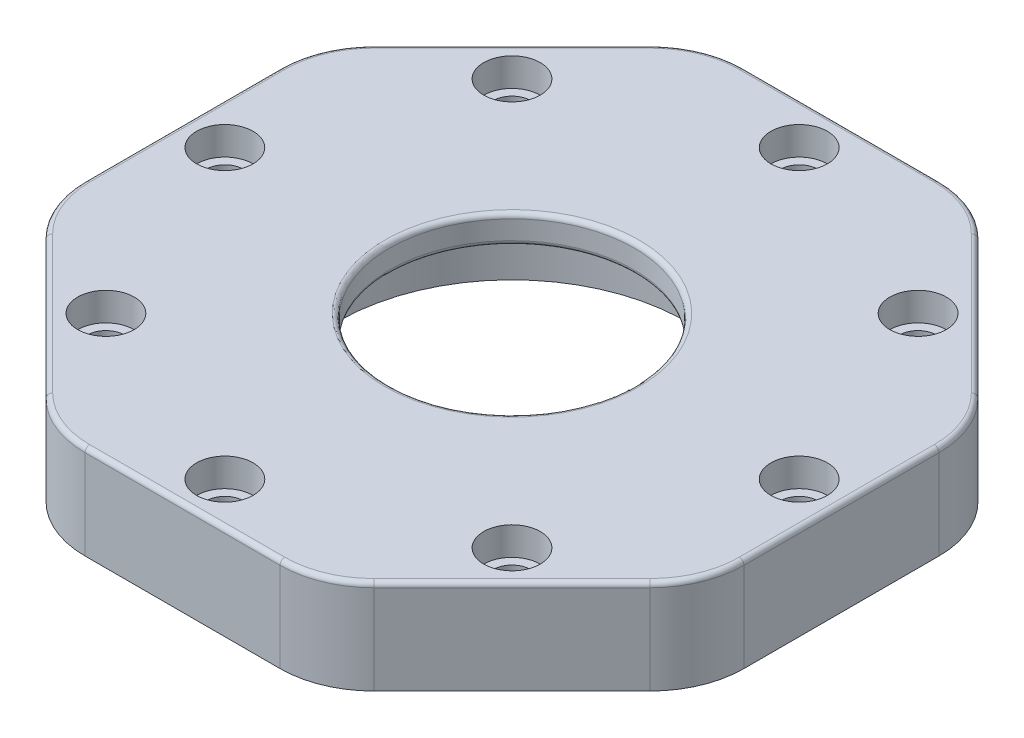
SolidWorks part; units mm, degrees
ref_plane "Front Plane" through (0, 0, 0) normal (0, 0, 1) x (1, 0, 0)
ref_plane "Top Plane" through (0, 0, 0) normal (0, 1, 0) x (1, 0, 0)
ref_plane "Right Plane" through (0, 0, 0) normal (1, 0, 0) x (0, 0, -1)
sketch "Sketch1" plane through (0, 0, 0) normal (0, 1, 0) x (1, 0, 0)
  line L0 (0, 0) -> (-47063.1739, 0) construction
  line L1 (0, 0) -> (0, -47063.1739) construction
  circle A0 centre (0, 0) radius 32
  dimension "D1" = 64
extrude "Boss-Extrude1" add sketch "Sketch1" along normal blind 10
sketch "Sketch2" plane through (0, 10, 0) normal (0, 1, 0) x (1, 0, 0)
  line L0 (0, 0) -> (-50000, 0) construction
  line L1 (0, 0) -> (0, -50000) construction
  circle A0 centre (0, 0) radius 18.5
  dimension "D1" = 37
extrude "Cut-Extrude1" cut sketch "Sketch2" along normal blind 7 from offset 10 offset against normal yes
sketch "Sketch3" plane through (0, 7, 0) normal (0, -1, 0) x (-1, 0, 0)
  line L0 (0, 0) -> (-50000, 0) construction
  line L1 (0, 0) -> (0, -50000) construction
  circle A0 centre (0, 0) radius 13
  dimension "D1" = 26
extrude "Cut-Extrude2" cut sketch "Sketch3" against normal through all
sketch "Sketch6" plane through (0, 0, 0) normal (0, 1, 0) x (1, 0, 0)
  line L0 (0, 0) -> (-50000, 0) construction
  line L1 (0, 0) -> (0, -50000) construction
  line L10 (10.3553, 35) -> (-10.3553, 35)
  line L11 (-17.4264, 32.0711) -> (-32.0711, 17.4264)
  line L12 (-35, 10.3553) -> (-35, -10.3553)
  line L13 (35, 10.3553) -> (35, -10.3553)
  line L14 (17.4264, 32.0711) -> (32.0711, 17.4264)
  line L15 (17.4264, -32.0711) -> (32.0711, -17.4264)
  line L16 (-17.4264, -32.0711) -> (-32.0711, -17.4264)
  line L17 (10.3553, -35) -> (-10.3553, -35)
  circle A10 centre (0, 0) radius 32 construction
  circle A11 centre (0, 0) radius 32
  circle A12 centre (0, 0) radius 35 construction
  arc A13 (-32.0711, 17.4264) -> (-35, 10.3553) centre (-25, 10.3553) ccw
  arc A14 (-32.0711, -17.4264) -> (-35, -10.3553) centre (-25, -10.3553) cw
  arc A15 (-17.4264, -32.0711) -> (-10.3553, -35) centre (-10.3553, -25) ccw
  arc A16 (17.4264, -32.0711) -> (10.3553, -35) centre (10.3553, -25) cw
  arc A17 (32.0711, -17.4264) -> (35, -10.3553) centre (25, -10.3553) ccw
  arc A18 (35, 10.3553) -> (32.0711, 17.4264) centre (25, 10.3553) ccw
  arc A19 (17.4264, 32.0711) -> (10.3553, 35) centre (10.3553, 25) ccw
  arc A20 (-10.3553, 35) -> (-17.4264, 32.0711) centre (-10.3553, 25) ccw
  point P9 (0, -35)
  point P16 (0, 35)
  point P19 (35, 0)
  point P20 (-35, 0)
  point P23 (-35, 14.4975)
  point P26 (-35, -14.4975)
  point P29 (-14.4975, -35)
  point P32 (14.4975, -35)
  point P35 (35, -14.4975)
  point P38 (35, 14.4975)
  point P41 (14.4975, 35)
  point P44 (-14.4975, 35)
  dimension "D1" = 70
  dimension "D2" = 10
fillet "Fillet2" radius 0.5 2 edges at (0, 10, -13) (0, 7, -13)
extrude "Boss-Extrude2" add sketch "Sketch6" along normal blind 10
sketch "Sketch7" plane through (0, 10, 0) normal (0, 1, 0) x (1, 0, 0)
  line L0 (0, 0) -> (-50000, 0) construction
  line L1 (0, 0) -> (0, -50000) construction
  line L2 (0, 0) -> (-35355.3391, 35355.3391) construction
  line L3 (-17.4264, 32.0711) -> (-32.0711, 17.4264) construction
  circle A0 centre (-21.5668, 21.5668) radius 2
  circle A1 centre (21.5668, 21.5668) radius 2
  circle A2 centre (21.5668, -21.5668) radius 2
  circle A3 centre (-21.5668, -21.5668) radius 2
  point P9 (-24.7487, 24.7487)
  point P21 (0, 0)
  dimension "D1" = 4
  dimension "D2" = 4.5
extrude "Cut-Extrude5" cut sketch "Sketch7" against normal through all
fillet "Fillet3" radius 0.5 16 edges at (-24.7487, 10, 24.7487) (-34.2388, 10, 14.1822) (-35, 10, 0) (-34.2388, 10, -14.1822) (-24.7487, 10, -24.7487) (-14.1822, 10, -34.2388) (0, 10, -35) (14.1822, 10, -34.2388) (24.7487, 10, -24.7487) (34.2388, 10, -14.1822) (35, 10, 0) (34.2388, 10, 14.1822) (24.7487, 10, 24.7487) (14.1822, 10, 34.2388) (0, 10, 35) (-14.1822, 10, 34.2388)
sketch "Sketch8" plane through (0, 10, 0) normal (0, 1, 0) x (1, 0, 0)
  line L0 (0, 0) -> (-50000, 0) construction
  line L1 (0, 0) -> (0, -50000) construction
  line L2 (0, 0) -> (-35355.3391, 35355.3391) construction
  circle A0 centre (-21.5668, 21.5668) radius 3
  circle A1 centre (21.5668, 21.5668) radius 3
  circle A2 centre (21.5668, -21.5668) radius 3
  circle A3 centre (-21.5668, -21.5668) radius 3
  point P19 (0, 0)
  dimension "D1" = 6
extrude "Cut-Extrude6" cut sketch "Sketch8" against normal blind 3
sketch "Sketch5" plane through (0, 10, 0) normal (0, 1, 0) x (1, 0, 0)
  line L0 (0, 0) -> (-50000, 0) construction
  line L1 (0, 0) -> (0, -50000) construction
  circle A0 centre (0, 0) radius 30.5 construction
  circle A1 centre (0, 30.5) radius 2
  circle A2 centre (30.5, 0) radius 2
  circle A3 centre (0, -30.5) radius 2
  circle A4 centre (-30.5, 0) radius 2
  point P18 (0, 0)
  dimension "D1" = 61
  dimension "D2" = 4
  dimension "D3" = 4
extrude "Cut-Extrude7" cut sketch "Sketch5" against normal through all
sketch "Sketch9" plane through (0, 10, 0) normal (0, 1, 0) x (1, 0, 0)
  line L0 (0, 0) -> (-50000, 0) construction
  line L1 (0, 0) -> (0, -50000) construction
  circle A0 centre (-30.5, 0) radius 3
  circle A1 centre (0, 30.5) radius 3
  circle A2 centre (30.5, 0) radius 3
  circle A3 centre (0, -30.5) radius 3
  point P17 (0, 0)
  dimension "D1" = 6
extrude "Cut-Extrude8" cut sketch "Sketch9" against normal blind 3
